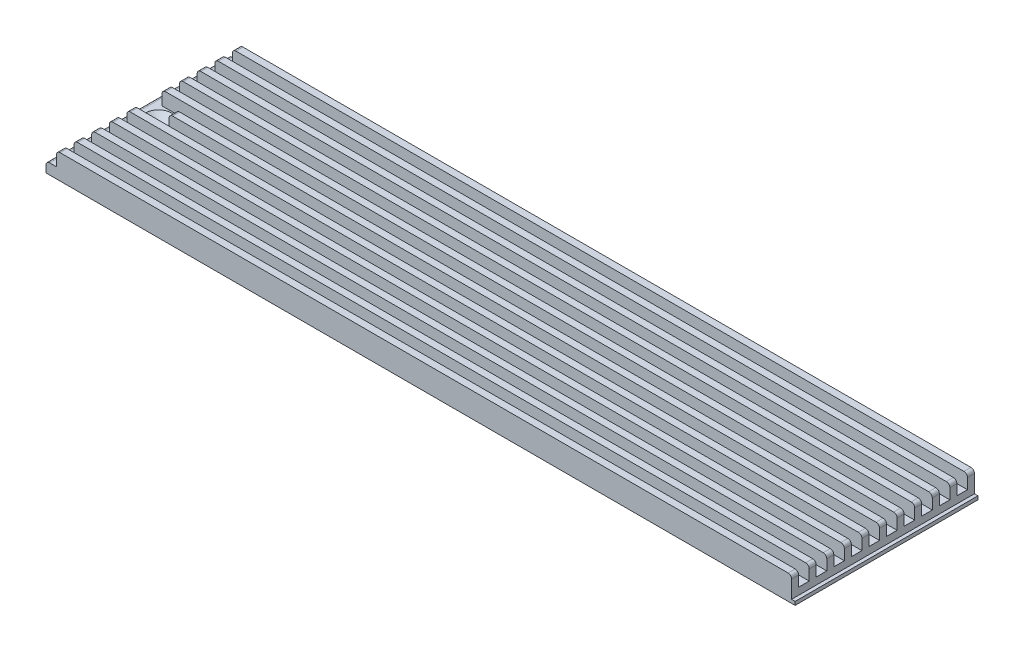
SolidWorks part; units mm, degrees
material "1060 Alloy"
ref_plane "Front Plane" through (0, 0, 0) normal (0, 0, 1) x (1, 0, 0)
ref_plane "Top Plane" through (0, 0, 0) normal (0, 1, 0) x (1, 0, 0)
ref_plane "Right Plane" through (0, 0, 0) normal (1, 0, 0) x (0, 0, -1)
sketch "Sketch1" plane through (0, 0, 0) normal (0, 1, 0) x (1, 0, 0)
  line L1 (0, 0) -> (106.5, 0)
  line L2 (0, 0) -> (0, -26)
  line L3 (0, -26) -> (106.5, -26)
  line L4 (106.5, 0) -> (106.5, -26)
  dimension "D1" = 106.5
  dimension "D2" = 26
extrude "Boss-Extrude1" add sketch "Sketch1" along normal blind 3.5 contours L2 L3 L4 L1
sketch "Sketch2" plane through (0, 0, 26) normal (0, 0, 1) x (1, 0, 0)
  line L0 (0, 0) -> (106.5, 0) construction
  line L1 (106.5, 3.5) -> (106, 3.5)
  line L2 (106.5, 3.5) -> (106.5, 0.5)
  line L3 (106.5, 0.5) -> (106, 0.5)
  line L4 (106, 3.5) -> (106, 0.5)
  line L6 (0, 3.5) -> (1.5, 3.5)
  line L7 (0, 3.5) -> (0, 1.5)
  line L8 (0, 1.5) -> (1.5, 1.5)
  line L9 (1.5, 3.5) -> (1.5, 1.5)
  dimension "D1" = 0.5
  dimension "D2" = 0.5
  dimension "D3" = 1.5
  dimension "D4" = 1.5
extrude "Cut-Extrude1" cut sketch "Sketch2" against normal through all
fillet "Fillet1" radius 0.5 3 edges at (1.5, 3.5, 13) (0, 1.5, 13) (106, 3.5, 13)
sketch "Sketch3" plane through (0, 3.5, 0) normal (0, 1, 0) x (1, 0, 0)
  line L0 (2, 0) -> (2, -26) construction
  line L1 (0.8191, -1) -> (108, -1)
  line L2 (0.8191, -1) -> (0.8191, -2.5)
  line L3 (0.8191, -2.5) -> (108, -2.5)
  line L4 (108, -1) -> (108, -2.5)
  line L5 (105.5, -26) -> (105.5, 0) construction
  line L6 (2, 0) -> (105.5, 0) construction
  line L7 (0.911, -3.5) -> (107.7103, -3.5)
  line L8 (0.911, -3.5) -> (0.911, -5)
  line L9 (0.911, -5) -> (107.7103, -5)
  line L10 (107.7103, -3.5) -> (107.7103, -5)
  line L11 (2, -13) -> (105.5, -13) construction
  line L12 (1.2169, -6) -> (107.7491, -6)
  line L13 (1.2169, -6) -> (1.2169, -7.5)
  line L14 (1.2169, -7.5) -> (107.7491, -7.5)
  line L15 (107.7491, -6) -> (107.7491, -7.5)
  line L16 (1.2169, -10) -> (107.7491, -10)
  line L17 (1.2169, -10) -> (1.2169, -8.5)
  line L18 (1.2169, -8.5) -> (107.7491, -8.5)
  line L19 (107.7491, -10) -> (107.7491, -8.5)
  line L20 (0.8191, -23.5) -> (108, -23.5)
  line L21 (106.5, -25) -> (108, -23.5)
  line L22 (0.8191, -25) -> (106.5, -25)
  line L23 (0.8191, -25) -> (0.8191, -23.5)
  line L24 (0.911, -22.5) -> (0.911, -21)
  line L25 (0.911, -21) -> (107.7103, -21)
  line L26 (107.7103, -22.5) -> (107.7103, -21)
  line L27 (0.911, -22.5) -> (107.7103, -22.5)
  line L28 (1.2169, -18.5) -> (107.7491, -18.5)
  line L29 (107.7491, -20) -> (107.7491, -18.5)
  line L30 (1.2169, -20) -> (107.7491, -20)
  line L31 (1.2169, -20) -> (1.2169, -18.5)
  line L32 (1.2169, -17.5) -> (107.7491, -17.5)
  line L33 (107.7491, -16) -> (107.7491, -17.5)
  line L34 (1.2169, -16) -> (107.7491, -16)
  line L35 (1.2169, -16) -> (1.2169, -17.5)
  line L36 (1.1408, -12.5) -> (107.8513, -12.5)
  line L37 (1.1408, -12.5) -> (1.1408, -11)
  line L38 (1.1408, -11) -> (107.8513, -11)
  line L39 (107.8513, -12.5) -> (107.8513, -11)
  line L40 (1.1408, -13.5) -> (1.1408, -15)
  line L41 (1.1408, -15) -> (107.8513, -15)
  line L42 (107.8513, -13.5) -> (107.8513, -15)
  line L43 (1.1408, -13.5) -> (107.8513, -13.5)
  line L44 (106.5, 0) -> (106.5, -26) construction
  dimension "D1" = 1.5
  dimension "D2" = 1
  dimension "D3" = 1
  dimension "D6" = 1.5
  dimension "D7" = 1
  dimension "D8" = 1.5
  dimension "D9" = 1
  dimension "D10" = 1.5
  dimension "D12" = 1
extrude "Cut-Extrude2" cut sketch "Sketch3" against normal blind 2
sketch "Sketch4" plane through (0, 1.5, 0) normal (0, 1, 0) x (1, 0, 0)
  line L1 (1.5, -12.5) -> (1.5, -13.5) construction
  line L2 (1.5, -11.2385) -> (5, -11.2385)
  line L3 (1.5, -11.2385) -> (1.5, -14.524)
  line L4 (1.5, -14.524) -> (5, -14.524)
  line L5 (5, -11.2385) -> (5, -14.524)
  dimension "D1" = 3.5
extrude "Cut-Extrude3" cut sketch "Sketch4" along normal up to surface (2 mm away)
hole_wizard "CSK for M1.6 Countersunk Flat Head Screw2" positions "3DSketch5" profile "Sketch10" countersink size "M1.6" standard "ISO"
sketch3d "3DSketch5"
  line L0 (106, 1.5, 11) -> (1.5, 1.5, 11) construction
  line L1 (0.5, 1.5, 0) -> (0.5, 1.5, 26) construction
  point P0 (3, 1.5, 13)
  dimension "D1" = 2
  dimension "D2" = 2.5
sketch "Sketch10" plane through (3, 1.5, 13) normal (1, 0, 0) x (0, 0, 1)
  line L0 (0, 0) -> (0, 15.5408)
  line L1 (0, 15.5408) -> (0.9, 15)
  line L2 (0.9, 15) -> (0.9, 0.9)
  line L3 (0.9, 0.9) -> (1.8, 0)
  line L5 (1.8, 0) -> (0, 0)
  line L6 (-0.9, 0.9) -> (-1.8, 0) construction
  line L10 (0, 15.5408) -> (-0.9, 15) construction
  line L11 (0, -6.35) -> (0, 107.95) construction
  dimension "Hole Dia." = 1.8
  dimension "Hole Depth" = 15
  dimension "Near C'Sink Dia." = 3.6
  dimension "Near C'Sink Angle" = 90
  dimension "Drill Angle" = 118
sketch "Sketch11" plane through (0, 0, 0) normal (0, -1, 0) x (1, 0, 0)
  line L0 (0, 0) -> (106.5, 0) construction
  line L1 (0, 0) -> (0, 26) construction
  circle A0 centre (7, 4.25) radius 0.5
  dimension "D1" = 1
  dimension "D2" = 4.25
  dimension "D3" = 7
extrude "Cut-Extrude4" cut sketch "Sketch11" against normal through all
fillet "Fillet2" radius 0.5 1 edges at (5, 3.5, 13)
